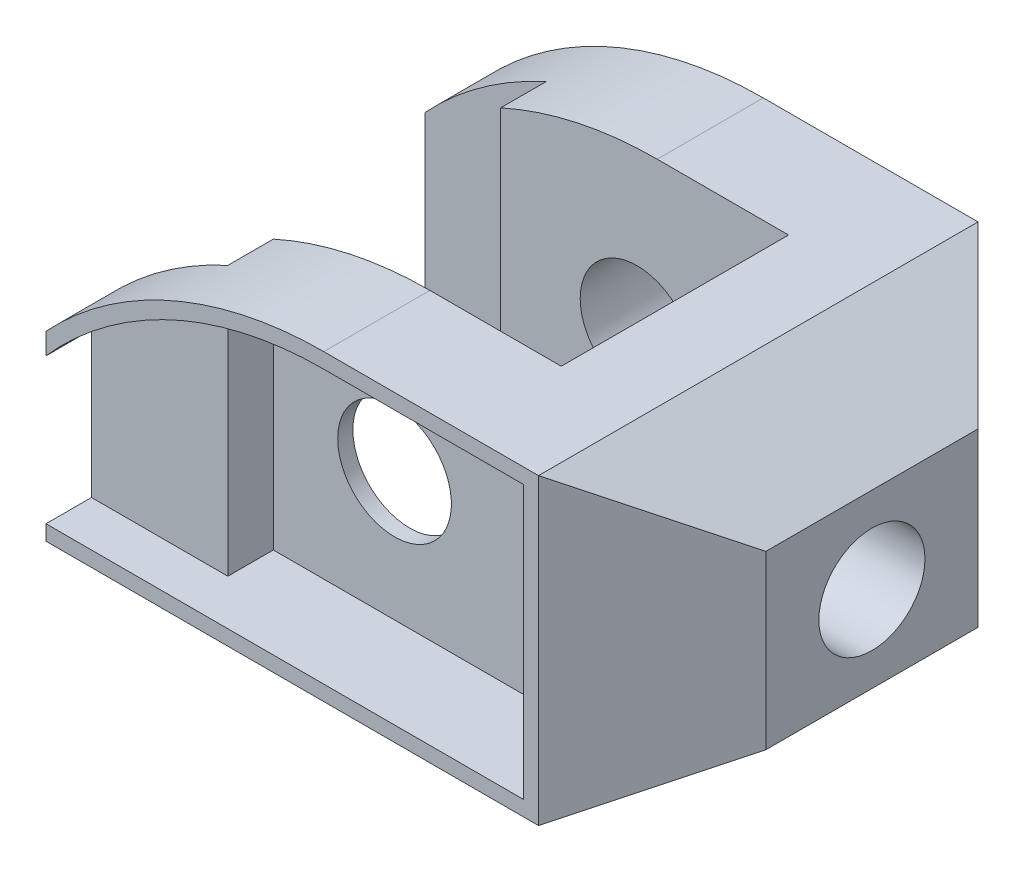
SolidWorks part; units mm, degrees
material "1060 Alloy"
ref_plane "Front Plane" through (0, 0, 0) normal (0, 0, 1) x (1, 0, 0)
ref_plane "Top Plane" through (0, 0, 0) normal (0, 1, 0) x (1, 0, 0)
ref_plane "Right Plane" through (0, 0, 0) normal (1, 0, 0) x (0, 0, -1)
sketch "Sketch1" plane through (0, 0, 0) normal (0, 0, 1) x (1, 0, 0)
  line L0 (0, 0) -> (-65, 0)
  line L1 (0, 0) -> (15, 8.6603)
  line L2 (15, 8.6603) -> (15, 31.3397)
  line L3 (15, 31.3397) -> (0, 40)
  line L4 (0, 40) -> (-28.3394, 40)
  line L5 (-65, 0) -> (-65, 24)
  arc A0 (-65, 24) -> (-28.3394, 40) centre (-28.3394, -10) cw
  circle A2 centre (-31, 19) radius 7.5
  dimension "D3" = 50
  dimension "D2" = 15
  dimension "D1" = 65
  dimension "D4" = 31
  dimension "D5" = 19
  dimension "D6" = 24
  dimension "D7" = 15
  dimension "D8" = 30
  dimension "D9" = 30
  dimension "D10" = 15
  dimension "D11" = 40
extrude "Boss-Extrude1" add sketch "Sketch1" along normal blind 58
ref_plane "Plane2" through (0, 20, 0) normal (0, 1, 0) x (1, 0, 0)
sketch "Sketch3" plane through (0, 20, 0) normal (0, 1, 0) x (1, 0, 0)
  line L0 (15, -29) -> (-80.6381, -29) construction
  line L1 (15, -58) -> (15, 0) construction
  line L2 (-11, -44) -> (-11, -14)
  line L3 (-11, -14) -> (-49, -14)
  line L4 (-49, -14) -> (-49, -8)
  line L5 (-49, -8) -> (-65, -8)
  line L6 (-65, -58) -> (-65, 0) construction
  line L7 (-65, -8) -> (-65, -50)
  line L8 (0, -58) -> (0, 0) construction
  line L9 (-28.3394, 0) -> (-65, 0) construction
  line L10 (-49, -50) -> (-65, -50)
  line L11 (-49, -44) -> (-49, -50)
  line L12 (-11, -44) -> (-49, -44)
  point P17 (-65, -29)
  point P20 (-11, -29)
  dimension "D1" = 11
  dimension "D2" = 16
  dimension "D3" = 6
  dimension "D4" = 8
extrude "Cut-Extrude1" cut sketch "Sketch3" against normal through all both and the other way through all
sketch "Sketch6" plane through (0, 0, 0) normal (0, 1, 0) x (1, 0, 0)
  line L0 (15, -29) -> (0, -29) construction
  line L1 (15, -58) -> (15, 0) construction
  line L2 (0, -58) -> (0, 0) construction
  line L3 (0, 0) -> (15, -15)
  line L4 (0, 0) -> (15, 0)
  line L5 (15, 0) -> (15, -15)
  line L6 (15, -58) -> (15, -43)
  line L7 (0, -58) -> (15, -58)
  line L8 (0, -58) -> (15, -43)
  dimension "D1" = 45
extrude "Cut-Extrude2" cut sketch "Sketch6" along normal through all both and the other way through all
sketch "Sketch7" plane through (15, 0, 0) normal (1, 0, 0) x (0, 0, -1)
  line L0 (0, 20) -> (-58, 20) construction
  line L1 (0, 40) -> (0, 0) construction
  line L2 (-58, 40) -> (-58, 0) construction
  line L3 (-58, 0) -> (0, 0) construction
  line L5 (-29, 40) -> (-29, 0) construction
  line L6 (-58, 40) -> (0, 40) construction
  circle A0 centre (-29, 20) radius 7
  dimension "D3" = 14
  dimension "D1" = 20
  dimension "D2" = 29
extrude "Cut-Extrude3" cut sketch "Sketch7" against normal through all both and the other way through all
sketch "Sketch8" plane through (0, 0, 58) normal (0, 0, 1) x (1, 0, 0)
  line L0 (-47, 34.2242) -> (-47, 2)
  line L1 (-65, 24) -> (-65, 0) construction
  line L14 (-2, 2) -> (-2, 38)
  line L15 (-65, 2) -> (-2, 2)
  line L16 (-2, 38) -> (-28.3394, 38)
  line L17 (-2, 2) -> (-2, 38)
  line L18 (-47, 2) -> (-2, 2)
  line L19 (-2, 38) -> (-28.3394, 38)
  arc A6 (-28.3394, 38) -> (-63.5336, 22.64) centre (-28.3394, -10) ccw
  arc A7 (-28.3394, 38) -> (-47, 34.2242) centre (-28.3394, -10) ccw
  dimension "D2" = 18
  dimension "D1" = 2
extrude "Cut-Extrude6" cut sketch "Sketch8" against normal blind 12
sketch "Sketch16" plane through (0, 0, 58) normal (0, 0, 1) x (1, 0, 0)
  line L0 (-65, 21.1865) -> (-65, 2)
  line L5 (-47, 2) -> (-65, 2)
  line L6 (-65, 24) -> (-65, 0) construction
  line L7 (-47, 2) -> (-47, 34.2242)
  arc A3 (-47, 34.2242) -> (-65, 21.1865) centre (-27.4075, -11.7696) ccw
  arc A4 (-28.3394, 40) -> (-65, 24) centre (-28.3394, -10) ccw construction
  dimension "D1" = 2
  dimension "D2" = 13.7696
extrude "Cut-Extrude7" cut sketch "Sketch16" against normal blind 6
equation "\"A\"= 58.00mm"
equation "\"B\"= 40.00mm"
equation "\"C\"= 65.00mm"
equation "\"D1@Sketch1\"=\"C\""
equation "\"D11@Sketch1\"=\"B\""
equation "\"D1@Boss-Extrude1\"=\"A\""
equation "\"D1@Sketch7\"=\"B\"/2"
equation "\"D2@Sketch7\"=\"A\"/2"
